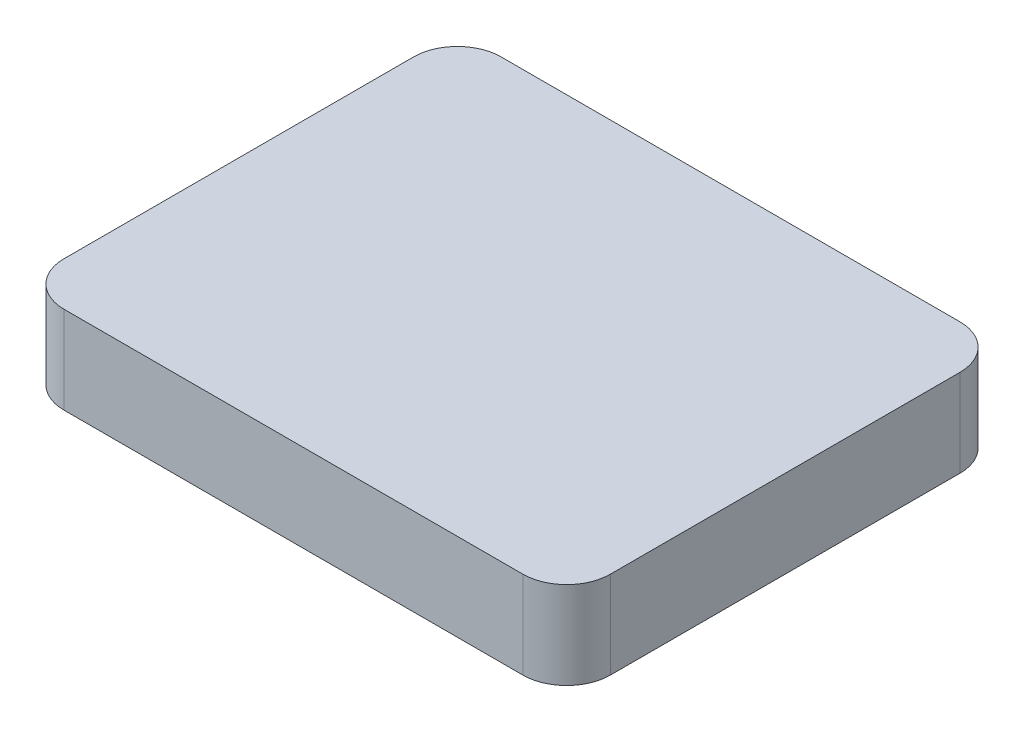
SolidWorks part; units mm, degrees
ref_plane "Front Plane" through (0, 0, 0) normal (0, 0, 1) x (1, 0, 0)
ref_plane "Top Plane" through (0, 0, 0) normal (0, 1, 0) x (1, 0, 0)
ref_plane "Right Plane" through (0, 0, 0) normal (1, 0, 0) x (0, 0, -1)
sketch "Sketch1" plane through (0, 0, 0) normal (0, 1, 0) x (1, 0, 0)
  line L1 (-125, 100) -> (125, 100)
  line L2 (-125, 100) -> (-125, -100)
  line L3 (-125, -100) -> (125, -100)
  line L4 (125, 100) -> (125, -100)
  line L5 (-125, 100) -> (125, -100) construction
  line L6 (-125, -100) -> (125, 100) construction
  point P0 (0, 0)
  dimension "D1" = 250
  dimension "D2" = 200
extrude "Boss-Extrude1" add sketch "Sketch1" along normal blind 40
fillet "Fillet1" radius 20 4 edges at (125, 20, 100) (-125, 20, -100) (125, 20, -100) (-125, 20, 100)
